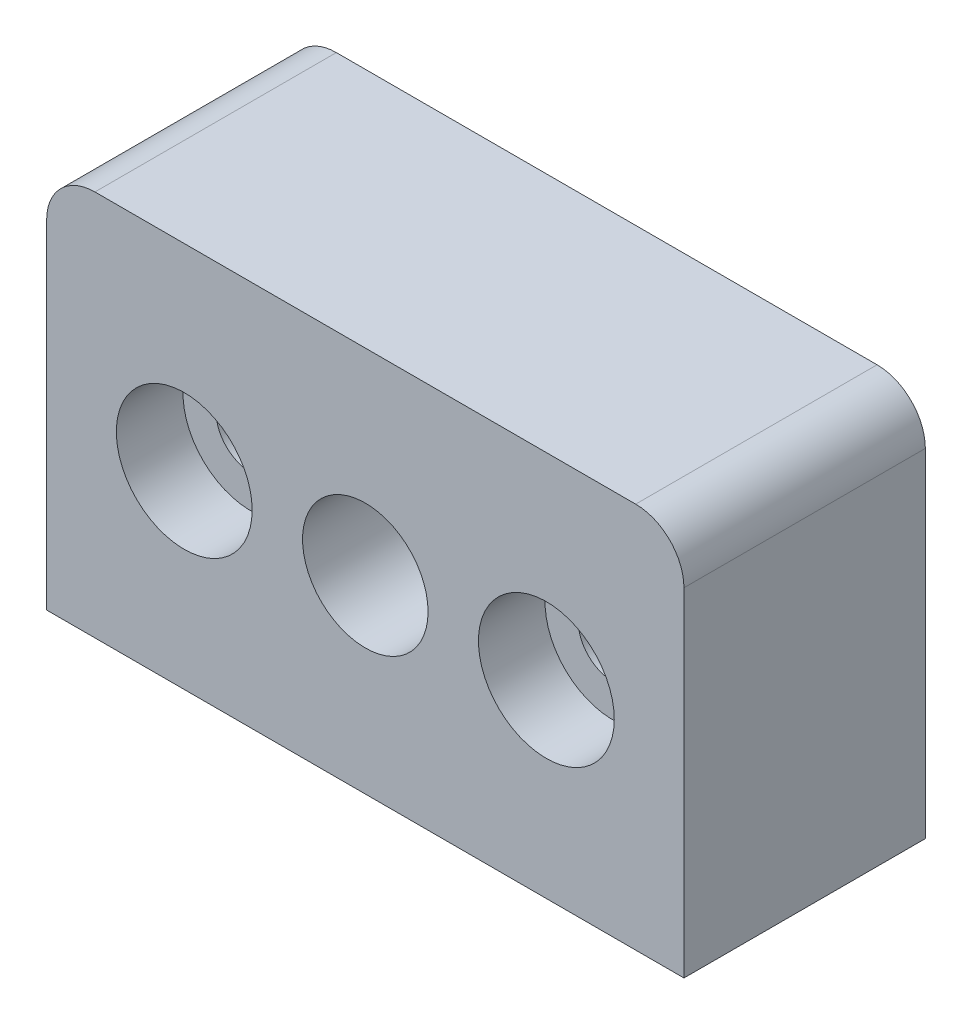
SolidWorks part; units mm, degrees
ref_plane "Front Plane" through (0, 0, 0) normal (0, 0, 1) x (1, 0, 0)
ref_plane "Top Plane" through (0, 0, 0) normal (0, 1, 0) x (1, 0, 0)
ref_plane "Right Plane" through (0, 0, 0) normal (1, 0, 0) x (0, 0, -1)
sketch "Sketch1" plane through (0, 0, 0) normal (0, 0, 1) x (1, 0, 0)
  line L1 (0, 0) -> (33.528, 0)
  line L2 (0, 0) -> (0, 20.32)
  line L3 (0, 20.32) -> (33.528, 20.32)
  line L4 (33.528, 0) -> (33.528, 20.32)
  dimension "D1" = 33.528
  dimension "D2" = 20.32
extrude "Boss-Extrude1" add sketch "Sketch1" along normal blind 12.7
sketch "Sketch2" plane through (0, 0, 12.7) normal (0, 0, 1) x (1, 0, 0)
  line L0 (0, 9.9568) -> (33.528, 9.9568) construction
  line L1 (0, 20.32) -> (0, 0) construction
  line L2 (33.528, 0) -> (33.528, 20.32) construction
  line L3 (0, 0) -> (33.528, 0) construction
  circle A0 centre (16.764, 9.9568) radius 3.302
  dimension "D2" = 6.604
  dimension "D1" = 9.9568
extrude "Cut-Extrude1" cut sketch "Sketch2" against normal blind 12.7
hole_wizard "CBORE for #6 Socket Head Cap Screw1" positions "Sketch3" profile "Sketch4" counterbore size "#6" standard "ANSI Inch" end condition through all
sketch "Sketch3" plane through (0, 0, 12.7) normal (0, 0, 1) x (1, 0, 0)
  line L0 (16.764, 9.9568) -> (33.528, 9.9568) construction
  line L1 (33.528, 0) -> (33.528, 20.32) construction
  line L3 (16.764, 9.9568) -> (0, 9.9568) construction
  line L4 (0, 20.32) -> (0, 0) construction
  circle A0 centre (16.764, 9.9568) radius 3.302 construction
  point P14 (7.239, 9.9568)
  point P16 (26.289, 9.9568)
  dimension "D2" = 9.525
  dimension "D1" = 9.525
sketch "Sketch4" plane through (26.289, 9.9568, 12.7) normal (1, 0, 0) x (0, -1, 0)
  line L0 (0, 0) -> (0, 12.7)
  line L1 (0, 12.7) -> (1.8288, 12.7)
  line L3 (1.8288, 12.7) -> (1.8288, 3.5052)
  line L4 (1.8288, 3.5052) -> (3.5725, 3.5052)
  line L5 (3.5725, 3.5052) -> (3.5725, 0)
  line L7 (3.5725, 0) -> (0, 0)
  line L11 (0, -6.35) -> (0, 107.95) construction
  dimension "Thru Hole Dia." = 3.6576
  dimension "Thru Hole Depth" = 12.7
  dimension "C'Bore Dia." = 7.145
  dimension "C'Bore Depth" = 3.5052
fillet "Fillet1" radius 2.54 2 edges at (0, 20.32, 6.35) (33.528, 20.32, 6.35)
hole_wizard "Tap Drill for #6-32 Tap1" positions "Sketch5" profile "Sketch7" hole size "#6-32" standard "ANSI Inch"
sketch "Sketch5" plane through (0, 0, 0) normal (0, -1, 0) x (-1, 0, 0)
  line L0 (0, -6.35) -> (-33.528, -6.35) construction
  line L1 (0, -12.7) -> (0, 0) construction
  line L2 (-33.528, -12.7) -> (-33.528, 0) construction
  line L4 (-16.764, -12.7) -> (-16.764, 0) construction
  line L5 (0, -12.7) -> (-33.528, -12.7) construction
  line L6 (0, 0) -> (-33.528, 0) construction
  point P16 (-11.43, -6.35)
  point P19 (-22.098, -6.35)
  dimension "D1" = 5.334
  dimension "D2" = 5.334
sketch "Sketch7" plane through (22.098, 0, 6.35) normal (1, 0, 0) x (0, 0, -1)
  line L0 (0, 0) -> (0, 8.4327)
  line L1 (0, 8.4327) -> (1.3525, 7.62)
  line L2 (1.3525, 7.62) -> (1.3525, 0)
  line L5 (1.3525, 0) -> (0, 0)
  line L10 (0, 8.4327) -> (-1.3526, 7.62) construction
  line L11 (0, -6.35) -> (0, 107.95) construction
  dimension "Hole Dia." = 2.7051
  dimension "Hole Depth" = 7.62
  dimension "Drill Angle" = 118
